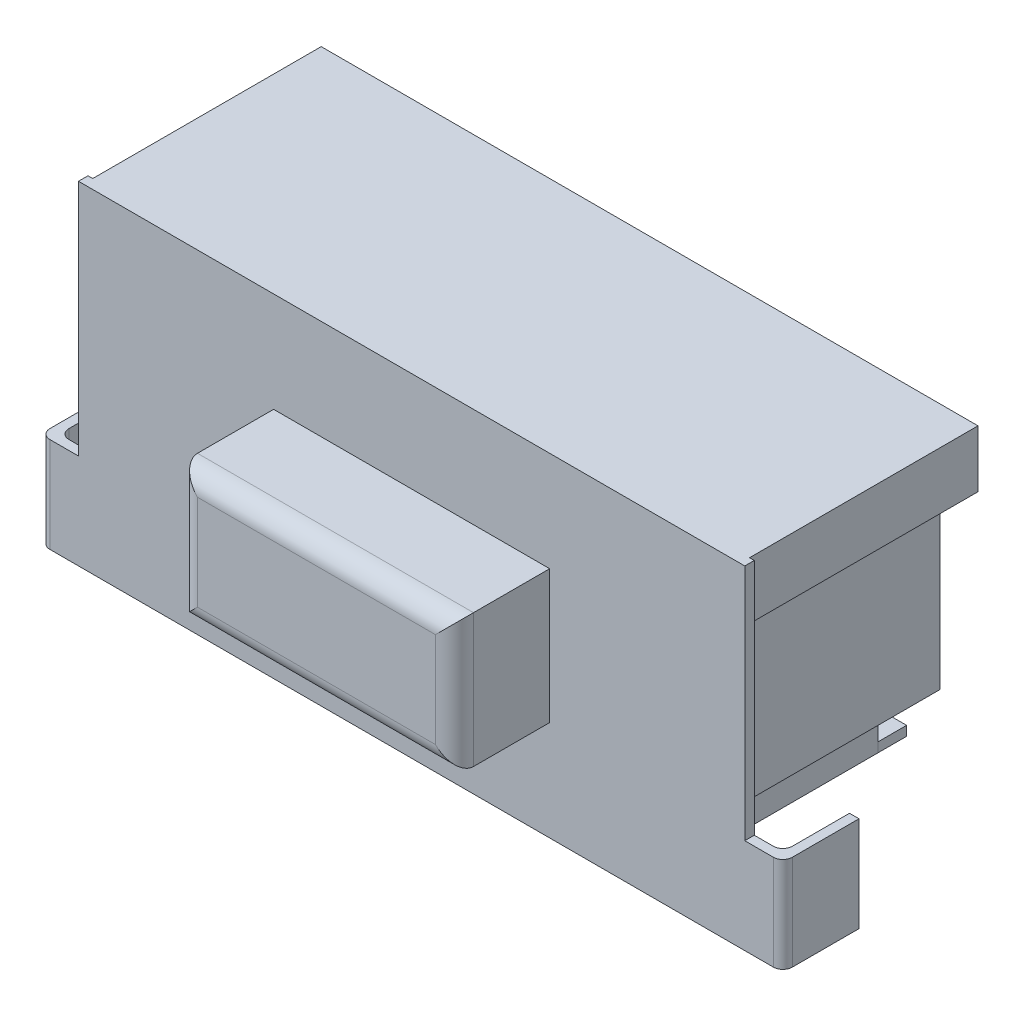
SolidWorks part; units mm, degrees
ref_plane "정면" through (0, 0, 0) normal (0, 0, 1) x (1, 0, 0)
ref_plane "윗면" through (0, 0, 0) normal (0, 1, 0) x (1, 0, 0)
ref_plane "우측면" through (0, 0, 0) normal (1, 0, 0) x (0, 0, -1)
sketch "스케치1" plane through (0, 0, 0) normal (0, 0, 1) x (1, 0, 0)
  line L0 (3.45, 2.9) -> (3.05, 2.9)
  line L1 (-3.45, 3.5) -> (3.45, 3.5)
  line L2 (-3.45, 3.5) -> (-3.45, 2.9)
  line L3 (-2.4, 0) -> (2.4, 0)
  line L4 (3.45, 3.5) -> (3.45, 2.9)
  line L5 (3.05, 2.9) -> (3.05, 0.9)
  line L6 (3.05, 0.9) -> (2.4, 0.9)
  line L7 (2.4, 0.9) -> (2.4, 0)
  line L8 (0, 0) -> (0, 4.5487) construction
  line L9 (-3.05, 0.9) -> (-2.4, 0.9)
  line L10 (-3.45, 2.9) -> (-3.05, 2.9)
  line L11 (-3.05, 2.9) -> (-3.05, 0.9)
  line L12 (-2.4, 0.9) -> (-2.4, 0)
  dimension "D1" = 6.9
  dimension "D2" = 3.5
  dimension "D3" = 4.8
  dimension "D4" = 6.1
  dimension "D5" = 0.6
  dimension "D6" = 2.6
extrude "보스-돌출1" add sketch "스케치1" against normal blind 2.5
sketch "스케치2" plane through (0, 0, 0) normal (0, 0, 1) x (1, 0, 0)
  line L0 (-3.5, 1) -> (-3.5, 3.5)
  line L1 (-3.9, 1) -> (-3.5, 1)
  line L2 (-3.9, 1) -> (-3.9, 0)
  line L3 (-3.9, 0) -> (3.9, 0)
  line L4 (3.9, 1) -> (3.9, 0)
  line L5 (-3.5, 3.5) -> (3.5, 3.5)
  line L6 (3.5, 3.5) -> (3.5, 1)
  line L7 (0, 0) -> (0, 4.1022) construction
  line L8 (3.5, 1) -> (3.9, 1)
  dimension "D1" = 7.8
  dimension "D2" = 1
  dimension "D3" = 7
  dimension "D4" = 3.5
extrude "보스-돌출2" add sketch "스케치2" against normal blind 0.1
sketch "스케치3" plane through (0, 0, 0) normal (0, 0, 1) x (1, 0, 0)
  line L0 (-3.9, 0) -> (3.9, 0) construction
  line L1 (3.9, 1) -> (3.8, 1)
  line L2 (3.9, 1) -> (3.9, 0)
  line L3 (3.9, 0) -> (3.8, 0)
  line L4 (3.8, 1) -> (3.8, 0)
  line L5 (0, 0) -> (0, 4.7817) construction
  line L6 (-3.9, 1) -> (-3.8, 1)
  line L7 (-3.9, 1) -> (-3.9, 0)
  line L8 (-3.9, 0) -> (-3.8, 0)
  line L9 (-3.8, 1) -> (-3.8, 0)
  dimension "D1" = 0.1
extrude "보스-돌출3" add sketch "스케치3" against normal blind 0.8
fillet "필렛1" radius 0.1 4 edges at (3.9, 0.5, 0) (3.8, 0.5, -0.1) (-3.8, 0.5, -0.1) (-3.9, 0.5, 0)
sketch "스케치4" plane through (0, 0, 0) normal (0, 1, 0) x (1, 0, 0)
  line L0 (0, 0) -> (0, 3.6037) construction
  line L1 (3.5, 0) -> (-3.5, 0) construction
  circle A0 centre (-1.15, 1) radius 0.4
  circle A1 centre (1.15, 1) radius 0.4
  dimension "D3" = 0.8
  dimension "D1" = 2.3
  dimension "D2" = 1
extrude "보스-돌출4" add sketch "스케치4" against normal blind 0.6
fillet "필렛2" radius 0.2 2 edges at (-1.15, -0.6, -0.6) (1.15, -0.6, -0.6)
sketch "스케치5" plane through (0, 0, 0) normal (0, 1, 0) x (1, 0, 0)
  line L0 (0, 0) -> (0, 3.2577) construction
  line L1 (-2.4, 2.8) -> (-1.8, 2.8)
  line L2 (-2.4, 2.8) -> (-2.4, 2.2)
  line L3 (-2.4, 2.2) -> (-1.8, 2.2)
  line L4 (-1.8, 2.8) -> (-1.8, 2.2)
  line L5 (1.8, 2.8) -> (2.4, 2.8)
  line L6 (1.8, 2.8) -> (1.8, 2.2)
  line L7 (1.8, 2.2) -> (2.4, 2.2)
  line L8 (2.4, 2.8) -> (2.4, 2.2)
  line L9 (3.5, 0) -> (-3.5, 0) construction
  line L10 (-2.4, 2.2) -> (-1.8, 2.8) construction
  line L11 (1.8, 2.8) -> (2.4, 2.2) construction
  point P12 (-2.1, 2.5)
  point P13 (2.1, 2.5)
  dimension "D1" = 0.6
  dimension "D2" = 4.2
  dimension "D3" = 2.5
extrude "보스-돌출5" add sketch "스케치5" along normal blind 0.1 separate body
sketch "스케치6" plane through (0, 0, 0) normal (0, 0, 1) x (1, 0, 0)
  line L0 (-1.45, 1.05) -> (1.45, 2.45) construction
  line L1 (-1.45, 2.45) -> (1.45, 2.45)
  line L2 (-1.45, 2.45) -> (-1.45, 1.05)
  line L3 (-1.45, 1.05) -> (1.45, 1.05)
  line L4 (1.45, 2.45) -> (1.45, 1.05)
  line L5 (0, 0) -> (0, 4.0272) construction
  line L6 (-3.8, 0) -> (3.8, 0) construction
  point P7 (0, 1.75)
  dimension "D1" = 1.75
  dimension "D2" = 1.4
  dimension "D3" = 2.9
extrude "보스-돌출6" add sketch "스케치6" along normal blind 1
fillet "필렛3" radius 0.2 4 edges at (0, 2.45, 1) (1.45, 1.75, 1) (0, 1.05, 1) (-1.45, 1.75, 1)
